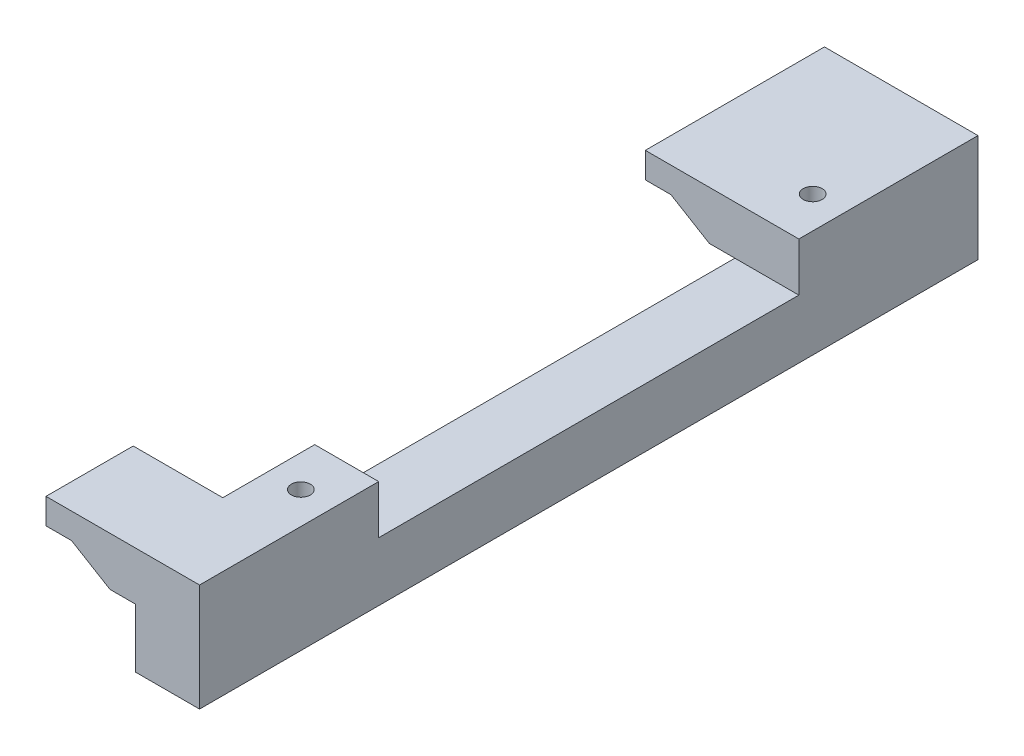
SolidWorks part; units mm, degrees
ref_plane "Front Plane" through (0, 0, 0) normal (0, 0, 1) x (1, 0, 0)
ref_plane "Top Plane" through (0, 0, 0) normal (0, 1, 0) x (1, 0, 0)
ref_plane "Right Plane" through (0, 0, 0) normal (1, 0, 0) x (0, 0, -1)
sketch "Sketch1" plane through (0, 0, 0) normal (0, 1, 0) x (1, 0, 0)
  line L0 (0, 139.035) -> (0, -139.035) construction
  line L1 (-112.62, 139.035) -> (112.62, 139.035)
  line L2 (-112.62, 139.035) -> (-112.62, -139.035)
  line L3 (-112.62, -139.035) -> (112.62, -139.035)
  line L4 (112.62, 139.035) -> (112.62, -139.035)
  point P6 (0, 0)
  dimension "D1" = 278.07
  dimension "D2" = 225.24
extrude "Boss-Extrude1" add sketch "Sketch1" along normal blind 10
sketch "Sketch4" plane through (0, 0, 139.035) normal (0, 0, 1) x (1, 0, 0)
  line L0 (-112.62, 10) -> (112.62, 10) construction
  line L1 (-38.63, 10) -> (-8.63, 10)
  line L2 (-38.63, 10) -> (-38.63, 31)
  line L3 (-38.63, 31) -> (-8.63, 31)
  line L4 (-8.63, 10) -> (-8.63, 31)
  line L5 (-112.62, 10) -> (-112.62, 0) construction
  dimension "D1" = 21
  dimension "D2" = 30
  dimension "D3" = 73.99
extrude "Boss-Extrude3" add sketch "Sketch4" against normal blind 152.09 separate body
sketch "Sketch5" plane through (0, 0, 139.035) normal (0, 0, 1) x (1, 0, 0)
  line L0 (-38.63, 10) -> (-21.13, 10)
  line L1 (-21.13, 10) -> (-21.13, 21.5)
  line L2 (-21.13, 21.5) -> (-26.13, 21.5)
  line L3 (-26.13, 21.5) -> (-33.63, 26)
  line L4 (-33.63, 26) -> (-38.63, 26)
  line L5 (-38.63, 31) -> (-38.63, 10) construction
  line L6 (-38.63, 26) -> (-38.63, 10)
  line L12 (-112.62, 10) -> (112.62, 10) construction
  dimension "D1" = 16
  dimension "D2" = 11.5
  dimension "D3" = 5
  dimension "D4" = 12.5
  dimension "D5" = 5
extrude "Cut-Extrude2" cut sketch "Sketch5" against normal up to surface (152.09 mm away) up to face at (-23.63, 20.5, -13.055)
ref_plane "Plane2" through (0, 17.25, 0) normal (0, 1, 0) x (1, 0, 0)
sketch "Sketch7" plane through (0, 17.25, 0) normal (0, 1, 0) x (1, 0, 0)
  line L1 (-21.13, -131.9073) -> (-21.13, -126.1627)
  line L3 (-8.63, -139.035) -> (-38.63, -139.035) construction
  line L4 (-21.13, 13.055) -> (-21.13, -139.035) construction
  arc A1 (-21.13, -131.9073) -> (-21.13, -126.1627) centre (-19.13, -129.035) cw
  dimension "D1" = 10
  dimension "D2" = 3.5
  dimension "D3" = 2
extrude "Boss-Extrude5" add sketch "Sketch7" along normal mid plane 3
sketch "Sketch8" plane through (0, 17.25, 0) normal (0, 1, 0) x (1, 0, 0)
  line L1 (-21.13, -7.8173) -> (-21.13, -2.0727)
  line L2 (-21.13, 13.055) -> (-21.13, -139.035) construction
  line L4 (-8.63, 13.055) -> (-38.63, 13.055) construction
  arc A3 (-21.13, -7.8173) -> (-21.13, -2.0727) centre (-23.13, -4.945) ccw
  dimension "D1" = 18
  dimension "D2" = 3.5
  dimension "D3" = 2
extrude "Cut-Extrude3" cut sketch "Sketch8" against normal mid plane 3.5
sketch "Sketch10" plane through (0, 0, 139.035) normal (0, 0, 1) x (1, 0, 0)
  line L1 (-112.62, 0) -> (112.62, 0)
  line L2 (-112.62, 0) -> (-112.62, 10)
  line L3 (-112.62, 10) -> (112.62, 10)
  line L4 (112.62, 0) -> (112.62, 10)
extrude "Cut-Extrude4" cut sketch "Sketch10" against normal through all
hole_wizard "Ø3.7 (3.7) Diameter Hole1" positions "Sketch11" profile "Sketch12" hole size "Ø3.7" standard "ANSI Metric" end condition up to next
sketch "Sketch11" plane through (0, 31, 0) normal (0, 1, 0) x (1, 0, 0)
  line L0 (-14.88, -112.99) -> (-14.88, -12.99) construction
  line L2 (-14.88, -62.99) -> (-8.63, -62.99) construction
  line L3 (-8.63, 13.055) -> (-8.63, -139.035) construction
  point P0 (-14.88, -12.99)
  point P2 (-14.88, -112.99)
  dimension "D1" = 6.25
  dimension "D2" = 100
sketch "Sketch12" plane through (-14.88, 31, 12.99) normal (1, 0, 0) x (0, 0, 1)
  line L0 (0, 0) -> (0, 21.001)
  line L1 (0, 21.001) -> (1.85, 21.001)
  line L2 (1.85, 21.001) -> (1.85, 0)
  line L5 (1.85, 0) -> (0, 0)
  line L11 (0, -6.35) -> (0, 107.95) construction
  dimension "Thru Hole Dia." = 3.7
  dimension "Thru Hole Depth" = 21.001
sketch "Sketch13" plane through (-8.63, 0, 0) normal (1, 0, 0) x (0, 0, -1)
  line L0 (13.055, 31) -> (-139.035, 31) construction
  line L1 (-104.035, 31) -> (-21.945, 31)
  line L2 (-104.035, 31) -> (-104.035, 21.5)
  line L3 (-104.035, 21.5) -> (-21.945, 21.5)
  line L4 (-21.945, 31) -> (-21.945, 21.5)
  line L5 (-139.035, 10) -> (-139.035, 31) construction
  line L6 (13.055, 10) -> (13.055, 31) construction
  line L7 (13.055, 21.5) -> (-139.035, 21.5) construction
  dimension "D1" = 35
  dimension "D2" = 35
extrude "Cut-Extrude5" cut sketch "Sketch13" against normal through all
sketch "Sketch14" plane through (-38.63, 0, 0) normal (-1, 0, 0) x (0, 0, 1)
  line L0 (104.035, 21.5) -> (139.035, 21.5) construction
  line L1 (104.035, 31) -> (121.995, 31)
  line L2 (104.035, 31) -> (104.035, 21.5)
  line L3 (104.035, 21.5) -> (121.995, 21.5)
  line L4 (121.995, 31) -> (121.995, 21.5)
  dimension "D1" = 17.96
extrude "Cut-Extrude6" cut sketch "Sketch14" against normal blind 17.5
